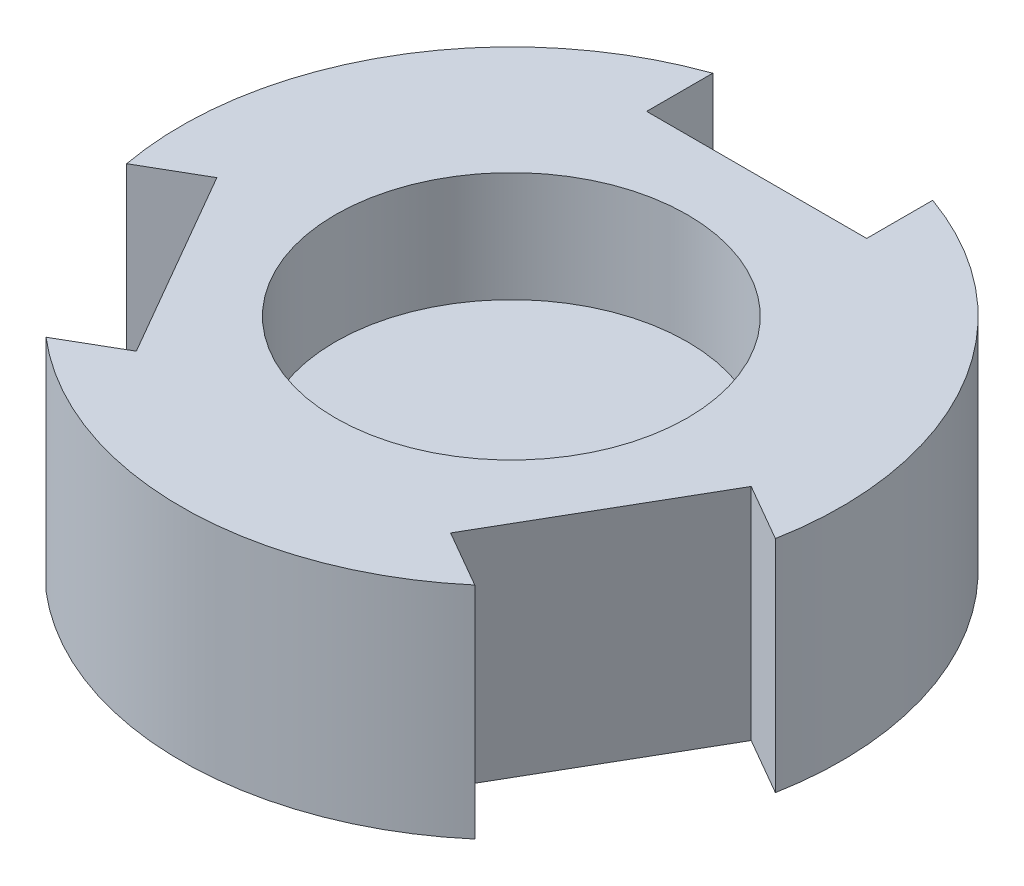
SolidWorks part; units mm, degrees
ref_plane "Front Plane" through (0, 0, 0) normal (0, 0, 1) x (1, 0, 0)
ref_plane "Top Plane" through (0, 0, 0) normal (0, 1, 0) x (1, 0, 0)
ref_plane "Right Plane" through (0, 0, 0) normal (1, 0, 0) x (0, 0, -1)
sketch "Sketch1" plane through (0, 0, 0) normal (0, 1, 0) x (1, 0, 0)
  circle A0 centre (0, 0) radius 15
extrude "Boss-Extrude1" add sketch "Sketch1" along normal blind 10
sketch "Sketch2" plane through (0, 10, 0) normal (0, 1, 0) x (1, 0, 0)
  circle A0 centre (0, 0) radius 8
extrude "Cut-Extrude1" cut sketch "Sketch2" against normal blind 5
sketch "Sketch3" plane through (0, 10, 0) normal (0, 1, 0) x (1, 0, 0)
  line L0 (-4.9931, 14.1397) -> (-4.9931, 16.5385)
  line L1 (-4.9931, 16.5385) -> (5.0069, 16.5385)
  line L3 (5.0069, 14.1397) -> (5.0069, 11.1397)
  line L4 (5.0069, 11.1397) -> (-4.9931, 11.1397)
  line L5 (-4.9931, 11.1397) -> (-4.9931, 14.1397)
  line L6 (5.0069, 16.5385) -> (5.0069, 14.1397)
  line L7 (9.7419, -11.4059) -> (7.1438, -9.9059)
  line L8 (7.1438, -9.9059) -> (12.1438, -1.2457)
  line L9 (12.1438, -1.2457) -> (14.7419, -2.7457)
  line L10 (14.7419, -2.7457) -> (16.8193, -3.9451)
  line L11 (16.8193, -3.9451) -> (11.8193, -12.6053)
  line L12 (11.8193, -12.6053) -> (9.7419, -11.4059)
  line L13 (-14.7488, -2.7338) -> (-12.1507, -1.2338)
  line L14 (-12.1507, -1.2338) -> (-7.1507, -9.894)
  line L15 (-7.1507, -9.894) -> (-9.7488, -11.394)
  line L16 (-9.7488, -11.394) -> (-11.8262, -12.5934)
  line L17 (-11.8262, -12.5934) -> (-16.8262, -3.9332)
  line L18 (-16.8262, -3.9332) -> (-14.7488, -2.7338)
  circle A1 centre (0, 0) radius 15 construction
  point P3 (0.0069, 15)
  point P24 (0, 0)
  dimension "D1" = 3
extrude "Cut-Extrude2" cut sketch "Sketch3" against normal up to next
